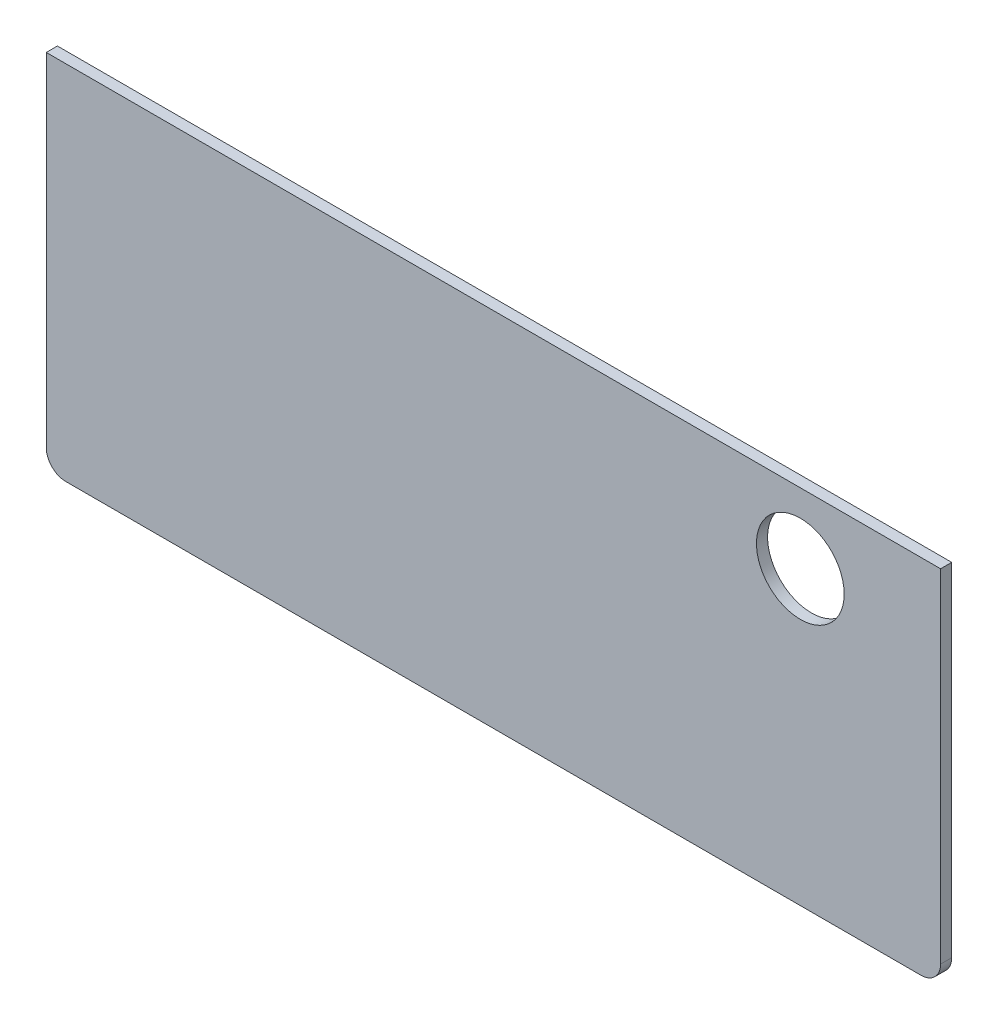
SolidWorks part; units mm, degrees
material "5052-H32"
ref_plane "Front Plane" through (0, 0, 0) normal (0, 0, 1) x (1, 0, 0)
ref_plane "Top Plane" through (0, 0, 0) normal (0, 1, 0) x (1, 0, 0)
ref_plane "Right Plane" through (0, 0, 0) normal (1, 0, 0) x (0, 0, -1)
sketch "Sketch1" plane through (0, 0, 0) normal (0, 0, 1) x (1, 0, 0)
  line L0 (-151.7654, 27.1868) -> (-151.7654, -75.9882)
  line L1 (-151.7654, -75.9882) -> (103.2346, -75.9882)
  line L2 (103.2346, -75.9882) -> (103.2346, 27.1868)
  line L3 (103.2346, 27.1868) -> (-151.7654, 27.1868)
  circle A0 centre (63.2346, 7.1868) radius 12.5
  point P8 (-58.3057, -12.819)
  dimension "D4" = 25
  dimension "D1" = 103.175
  dimension "D2" = 255
  dimension "D3" = 20
  dimension "D5" = 40
extrude "Boss-Extrude1" add sketch "Sketch1" along normal blind 3.175
fillet "Fillet1" radius 5.5562 2 edges at (-151.7654, -75.9882, 1.5875) (103.2346, -75.9882, 1.5875)
equation "\"L\"= 420mm"
equation "\"W\"= 255mm"
equation "\"H\"= 110mm"
equation "\"Compartment Width\"= 80"
equation "\"T\"= 4.7625 * 2 / 3mm"
equation "\"Inside Fillet Radius\"= 5.55625mm"
equation "\"D1@Boss-Extrude1\"=\"T\""
equation "\"D1@Fillet1\"=\"Inside Fillet Radius\""
equation "\"Hole\"=25mm"
equation "\"D4@Sketch1\"=\"Hole\""
equation "\"D2@Sketch1\"=\"W\""
equation "\"D1@Sketch1\"=\"H\"+\"T\"-10"
equation "\"Offset\"= 16mm"
equation "\"Wheel to Wall\"= 43"
